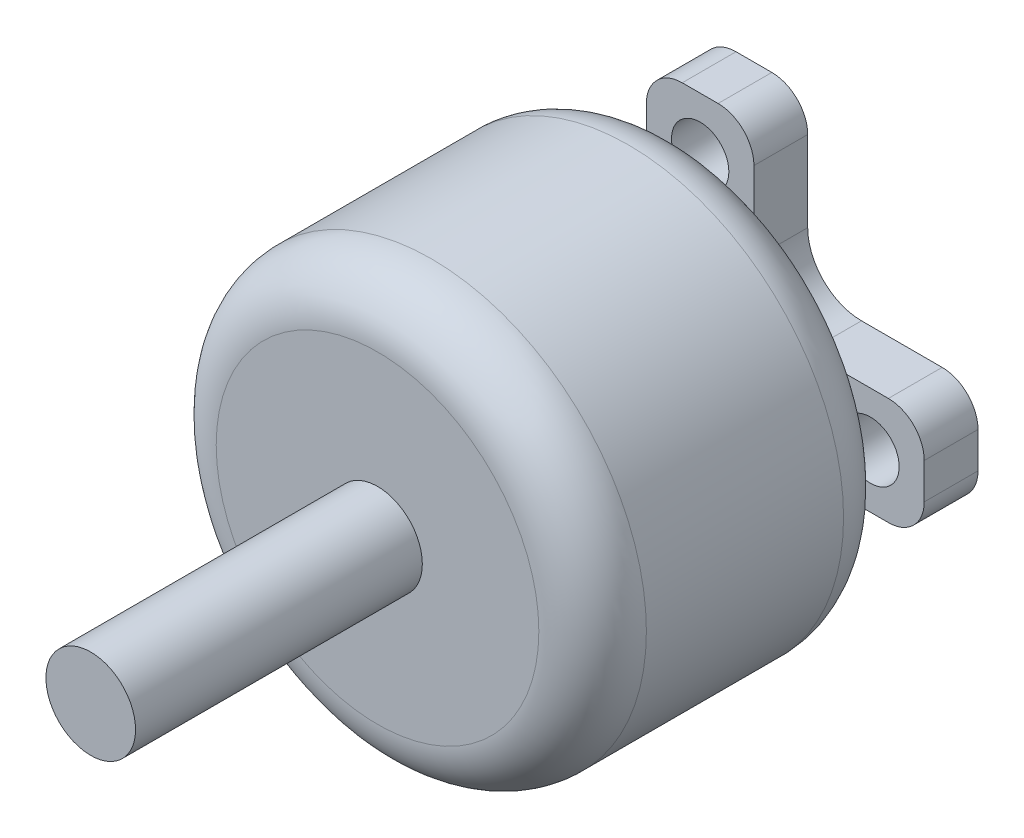
SolidWorks part; units mm, degrees
ref_plane "Front Plane" through (0, 0, 0) normal (0, 0, 1) x (1, 0, 0)
ref_plane "Top Plane" through (0, 0, 0) normal (0, 1, 0) x (1, 0, 0)
ref_plane "Right Plane" through (0, 0, 0) normal (1, 0, 0) x (0, 0, -1)
sketch "Sketch1" plane through (0, 0, 0) normal (0, 0, 1) x (1, 0, 0)
  line L0 (-71.7817, -74.7817) -> (-67.2817, -74.7817)
  line L1 (-78.7817, -65.2817) -> (-76.7817, -65.2817)
  line L2 (-80.7817, -67.2817) -> (-80.7817, -71.7817)
  line L3 (-78.7817, -90.2817) -> (-76.7817, -90.2817)
  line L4 (-74.7817, -67.2817) -> (-74.7817, -71.7817)
  line L5 (-88.2817, -74.7817) -> (-83.7817, -74.7817)
  line L6 (-90.2817, -76.7817) -> (-90.2817, -78.7817)
  line L7 (-88.2817, -80.7817) -> (-83.7817, -80.7817)
  line L8 (-65.2817, -76.7817) -> (-65.2817, -78.7817)
  line L9 (-80.7817, -83.7817) -> (-80.7817, -88.2817)
  line L10 (-74.7817, -83.7817) -> (-74.7817, -88.2817)
  line L11 (-71.7817, -80.7817) -> (-67.2817, -80.7817)
  arc A4 (-80.7817, -83.7817) -> (-83.7817, -80.7817) centre (-83.7817, -83.7817) ccw
  arc A5 (-74.7817, -83.7817) -> (-71.7817, -80.7817) centre (-71.7817, -83.7817) cw
  arc A6 (-71.7817, -74.7817) -> (-74.7817, -71.7817) centre (-71.7817, -71.7817) cw
  arc A7 (-83.7817, -74.7817) -> (-80.7817, -71.7817) centre (-83.7817, -71.7817) ccw
  arc A8 (-78.7817, -65.2817) -> (-80.7817, -67.2817) centre (-78.7817, -67.2817) ccw
  arc A9 (-76.7817, -65.2817) -> (-74.7817, -67.2817) centre (-76.7817, -67.2817) cw
  arc A10 (-67.2817, -74.7817) -> (-65.2817, -76.7817) centre (-67.2817, -76.7817) cw
  arc A11 (-67.2817, -80.7817) -> (-65.2817, -78.7817) centre (-67.2817, -78.7817) ccw
  arc A12 (-76.7817, -90.2817) -> (-74.7817, -88.2817) centre (-76.7817, -88.2817) ccw
  arc A13 (-80.7817, -88.2817) -> (-78.7817, -90.2817) centre (-78.7817, -88.2817) ccw
  arc A14 (-90.2817, -78.7817) -> (-88.2817, -80.7817) centre (-88.2817, -78.7817) ccw
  arc A15 (-88.2817, -74.7817) -> (-90.2817, -76.7817) centre (-88.2817, -76.7817) ccw
  circle A16 centre (-77.7817, -68.2817) radius 1.6
  circle A17 centre (-68.2817, -77.7817) radius 1.6
  circle A18 centre (-77.7817, -87.2817) radius 1.6
  circle A19 centre (-87.2817, -77.7817) radius 1.6
  point P24 (-74.7817, -80.7817)
  point P39 (-74.7817, -90.2817)
  point P42 (-80.7817, -90.2817)
  point P45 (-90.2817, -80.7817)
  point P48 (-90.2817, -74.7817)
  dimension "D9" = 3
  dimension "D10" = 2
  dimension "D2" = 6
  dimension "D3" = 6
extrude "Boss-Extrude1" add sketch "Sketch1" along normal blind 3
sketch "Sketch2" plane through (0, 0, 3) normal (0, 0, 1) x (1, 0, 0)
  line L0 (-77.7817, -68.2817) -> (-77.7817, -77.7817) construction
  line L1 (-68.2817, -77.7817) -> (-77.7817, -77.7817) construction
  circle A0 centre (-77.7817, -77.7817) radius 2.852
extrude "Boss-Extrude2" add sketch "Sketch2" along normal blind 1
sketch "Sketch3" plane through (0, 0, 4) normal (0, 0, 1) x (1, 0, 0)
  circle A0 centre (-77.7817, -77.7817) radius 12
extrude "Boss-Extrude3" add sketch "Sketch3" along normal blind 17
sketch "Sketch4" plane through (0, 0, 21) normal (0, 0, 1) x (1, 0, 0)
  circle A0 centre (-77.7817, -77.7817) radius 2.5
extrude "Boss-Extrude4" add sketch "Sketch4" along normal blind 16
fillet "Fillet1" radius 3 2 edges at (-65.7817, -77.7817, 21) (-65.7817, -77.7817, 4)
